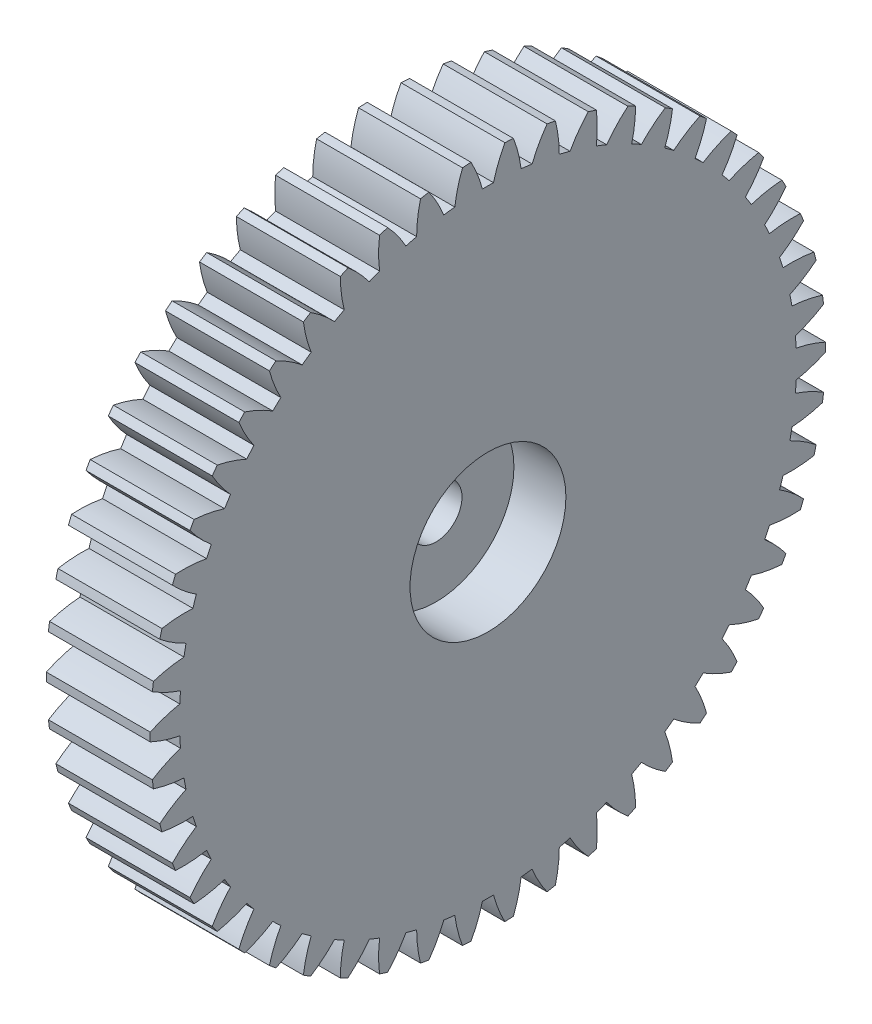
SolidWorks part; units mm, degrees
material "ABS"
ref_plane "Plane1" through (0, 0, 0) normal (0, 0, 1) x (1, 0, 0)
ref_plane "Plane2" through (0, 0, 0) normal (0, 1, 0) x (1, 0, 0)
ref_plane "Plane3" through (0, 0, 0) normal (1, 0, 0) x (0, 0, -1)
sketch "HoldingSke" plane through (0, 0, 0) normal (0, 1, 0) x (1, 0, 0)
  line L0 (0, 0) -> (2.5712, -3.0642)
  line L1 (-15, 0) -> (100, 0) construction
  line L2 (0, 0) -> (-2.1039, 2.3779)
  line L3 (0, 0) -> (-11.863, 4.5341)
  line L4 (0, 0) -> (5.5511, 6.6156)
  line L5 (0, 0) -> (-46.8476, -17.4728)
  line L6 (0, 0) -> (-1.6579, -1.1186)
  line L7 (-2.1039, 2.3779) -> (8.6586, 51.2059)
  line L8 (-76.2, 54.61) -> (-76.1, 54.61)
  line L9 (-71.009, 38.7566) -> (-53.1078, 45.2721)
  line L10 (-76.2, 71.12) -> (104.1128, 71.12)
  line L11 (0, 0) -> (-2, 0)
  line L12 (-76.2, 101.6) -> (-76.192, 101.6)
  line L13 (24.9733, 27.94) -> (52.9518, 28.4284)
  line L14 (24.9733, 27.94) -> (24.9743, 27.94)
  line L15 (24.9733, 27.94) -> (100.4006, 29.5858)
  line L16 (-63.627, -0.25) -> (-12.827, -0.25)
  circle A0 centre (0, 0) radius 0.5
  circle A1 centre (0, 0) radius 5.9365
  circle A2 centre (0, 0) radius 37.5
  circle A3 centre (0, 0) radius 0.5
  dimension "MHD" = 11.873
  dimension "Hub_dia" = 75
  dimension "Bore" = 1
  dimension "MBD" = 1
  dimension "Num_teeth" = 50
  dimension "Pitch" = 4
  dimension "Overall_len" = 50
  dimension "Show_teeth" = 50
  dimension "Thickness" = 2
  dimension "OAL" = 50.0001
  dimension "T_dim" = 0.1
  dimension "Ap" = 20
  dimension "H" = 19.05
  dimension "Pitch_radius" = 180.3128
  dimension "Width" = 2
  dimension "Backlash" = 0.008
  dimension "Addendum_fac" = 1
  dimension "Dedendum_fac" = 1.25
  dimension "Clearance_fac" = 0.25
  dimension "Dedendum_add" = 0.001
  dimension "Module" = 0.25
sketch "BasProSke" plane through (0, 0, 0) normal (0, 1, 0) x (1, 0, 0)
  line L0 (-10, 0) -> (60, 0) construction
  line L1 (0, 0) -> (0, 6.5)
  line L2 (0, 0) -> (2, 0)
  line L3 (2, 0) -> (2, 6.5)
  line L4 (2, 6.5) -> (0, 6.5)
  dimension "Thickness" = 2
  dimension "Diameter" = 13
revolve "Base-Revolve" add sketch "BasProSke" angle 360 about L0
sketch "TooCutSke" plane through (0, 0, 0) normal (1, 0, 0) x (0, 0, -1)
  line L1 (0, 0) -> (0, 107) construction
  line L2 (0, 0) -> (-0.2103, 6.2465) construction
  line L3 (0, 0) -> (-0.7845, 12.47) construction
  line L4 (-0.2103, 6.2465) -> (-0.3923, 6.235) construction
  arc A0 (0.1067, 5.9355) -> (-0.1067, 5.9355) centre (0, 0) ccw
  arc A1 (0.3398, 6.5165) -> (-0.3398, 6.5165) centre (0, 0) ccw
  circle A2 centre (0, 0) radius 6.25 construction
  circle A3 centre (0, 0) radius 5.8731 construction
  arc A4 (-0.1067, 5.9355) -> (-0.3398, 6.5165) centre (-2.5252, 5.3025) ccw
  arc A5 (0.3398, 6.5165) -> (0.1067, 5.9355) centre (2.5252, 5.3025) ccw
  dimension "Root_dia" = 11.873
  dimension "Overcut_dia" = 13.0508
  dimension "Pitch_dia" = 12.5
  dimension "Base_dia" = 11.7462
  dimension "Flank_rad" = 2.5
  dimension "Half_ang" = 3.6
  dimension "Half_CT" = 0.1823
extrude "ToothCut" cut sketch "TooCutSke" along normal through all
fillet "Breaks" [suppressed] radius 0.005
fillet "RootFillets" [suppressed] radius 0.0635
pattern_circular "TeethCuts" count 50 every 7.2 about axis through (-10, 0, 0) along (1, 0, 0) of "ToothCut", "RootFillets", "Breaks"
sketch "HubNeaOneSke" plane through (0, 0, 0) normal (-1, 0, 0) x (0, 0, 1)
  circle A0 centre (0, 0) radius 5.9365
  dimension "Diameter" = 11.873
extrude "HubNearOne" [suppressed] add sketch "HubNeaOneSke" along normal blind 48.0001
sketch "HubNeaBotSke" plane through (0, 0, 0) normal (-1, 0, 0) x (0, 0, 1)
  circle A0 centre (0, 0) radius 5.9365
  dimension "Diameter" = 11.873
extrude "HubNearBoth" [suppressed] add sketch "HubNeaBotSke" along normal blind 24
ref_plane "FarPln" through (2, 0, 0) normal (1, 0, 0) x (0, 0, -1)
sketch "HubFarSke" plane through (2, 0, 0) normal (1, 0, 0) x (0, 0, -1)
  circle A0 centre (0, 0) radius 5.9365
  dimension "Diameter" = 11.873
extrude "HubFar" [suppressed] add sketch "HubFarSke" along normal blind 24
sketch "BorSke" plane through (0, 0, 0) normal (1, 0, 0) x (0, 0, -1)
  circle A0 centre (0, 0) radius 0.5
  dimension "Diameter" = 1
extrude "Bore" cut sketch "BorSke" along normal mid plane 100.0001
sketch "KeySke" plane through (0, 0, 0) normal (1, 0, 0) x (0, 0, -1)
  line L0 (-0.05, 0) -> (-0.05, 0.6)
  line L1 (-0.05, 0.6) -> (0.05, 0.6)
  line L2 (0.05, 0.6) -> (0.05, 0)
  line L3 (0, 0) -> (0, 34) construction
  line L4 (-0.05, 0) -> (0.05, 0)
  dimension "Offset" = 0.6
  dimension "Width" = 0.1
extrude "Keyway" [suppressed] cut sketch "KeySke" along normal mid plane 100.0001
pattern_circular "Keyway2" [suppressed] count 2 every 90 about axis through (-10, 0, 0) along (1, 0, 0)
sketch "Sketch1" plane through (2, 0, 0) normal (1, 0, 0) x (0, 0, -1)
  circle A0 centre (0, 0) radius 1.5
  dimension "D1" = 3
extrude "Cut-Extrude1" cut sketch "Sketch1" against normal blind 1
equation "' \"Module@HoldingSke\" = 6.35"
equation "' \"Num_teeth@HoldingSke\" = 12"
equation "' \"Ap@HoldingSke\" =  20"
equation "' \"Ap@HoldingSke\" = 20"
equation "' \"Width@HoldingSke\" = 0.5 * 25.4"
equation "' \"Hub_dia@HoldingSke\"= 1 * 25.4"
equation "' \"Hub_dia@HoldingSke\" = 1 * 25.4"
equation "' \"Overall_len@HoldingSke\" = 1.0 * 25.4"
equation "' \"Bore@HoldingSke\" = 0.75 * 25.4"
equation "' \"T_dim@HoldingSke\" = 0.1 * 25.4"
equation "' \"Width@KeySke\" = 0.25 * 25.4"
equation "' \"Show_teeth@HoldingSke\" = 13"
equation "' \"Backlash@HoldingSke\" = 0.009 * 25.4"
equation "' \"Addendum_fac@HoldingSke\" = 1.0"
equation "' \"Dedendum_fac@HoldingSke\" = 1.25"
equation "' \"Dedendum_add@HoldingSke\" = 0.00005 * 25.4"
equation "' \"Clearance_fac@HoldingSke\" = 0.25"
equation "\"Pitch@HoldingSke\" = 1 / \"Module@HoldingSke\""
equation "\"Overcut_dia@TooCutSke\" = (\"Num_teeth@HoldingSke\" + 2 * \"Addendum_fac@HoldingSke\") / \"Pitch@HoldingSke\" + 0.002 * 25.4"
equation "\"Pitch_dia@TooCutSke\" = \"Num_teeth@HoldingSke\" / \"Pitch@HoldingSke\""
equation "\"Base_dia@TooCutSke\" = \"Num_teeth@HoldingSke\" / \"Pitch@HoldingSke\" * cos((\"Ap@HoldingSke\"  * 3.14159265 / 180))"
equation "\"Root_dia@TooCutSke\" = (\"Num_teeth@HoldingSke\" + 2) / \"Pitch@HoldingSke\" - 2 * (\"Addendum_fac@HoldingSke\" + \"Dedendum_fac@HoldingSke\") / \"Pitch@HoldingSke\" - \"Dedendum_add@HoldingSke\" * 2"
equation "\"Half_ang@TooCutSke\" = 180 / \"Num_teeth@HoldingSke\""
equation "\"Half_CT@TooCutSke\" = \"Num_teeth@HoldingSke\" / \"Pitch@HoldingSke\" * sin((3.14159265 / 2 / \"Num_teeth@HoldingSke\")) / 2 - 7 * \"Backlash@HoldingSke\" / 4"
equation "\"Flank_rad@TooCutSke\" = \"Num_teeth@HoldingSke\" / \"Pitch@HoldingSke\" / 5"
equation "\"Radius@RootFillets\" = \"Clearance_fac@HoldingSke\" / \"Pitch@HoldingSke\" + \"Dedendum_add@HoldingSke\""
equation "\"Break_rad@Breaks\" = 0.02 / \"Pitch@HoldingSke\""
equation "\"Thickness@HoldingSke\" = \"Width@HoldingSke\""
equation "\"OAL@HoldingSke\" = \"Thickness@HoldingSke\""
equation "\"MHD@HoldingSke\" = (\"Num_teeth@HoldingSke\" + 2) / \"Pitch@HoldingSke\" - 2 * (\"Addendum_fac@HoldingSke\" + \"Dedendum_fac@HoldingSke\")  / \"Pitch@HoldingSke\" - \"Dedendum_add@HoldingSke\" * 2"
equation "\"MBD@HoldingSke\" = (\"Num_teeth@HoldingSke\" + 2) / \"Pitch@HoldingSke\" - 2 * (\"Addendum_fac@HoldingSke\" + \"Dedendum_fac@HoldingSke\")  / \"Pitch@HoldingSke\" - \"Dedendum_add@HoldingSke\" * 2 - 0.002 * 25.4"
equation "\"MHD@HoldingSke\" = ((sgn( \"MHD@HoldingSke\" - \"Hub_dia@HoldingSke\" )-1)*( \"MHD@HoldingSke\" - \"Hub_dia@HoldingSke\" ))/-2+ \"Hub_dia@HoldingSke\""
equation "\"MBD@HoldingSke\" = ((sgn( \"MBD@HoldingSke\" - \"Bore@HoldingSke\" )-1)*( \"MBD@HoldingSke\" - \"Bore@HoldingSke\" ))/-2+ \"Bore@HoldingSke\""
equation "\"OAL@HoldingSke\" = ((sgn( \"OAL@HoldingSke\" - \"Overall_len@HoldingSke\" )+1)*( \"OAL@HoldingSke\" - \"Overall_len@HoldingSke\" ))/2 + \"Overall_len@HoldingSke\" + 0.000002 * 25.4"
equation "\"Num_teeth@TeethCuts\" = int( \"Show_teeth@HoldingSke\" ) + 1"
equation "\"Num_teeth@TeethCuts\" = ((sgn( \"Num_teeth@TeethCuts\" - \"Num_teeth@HoldingSke\" )-1)*( \"Num_teeth@TeethCuts\" - \"Num_teeth@HoldingSke\" ))/-2+ \"Num_teeth@HoldingSke\""
equation "\"Num_teeth@TeethCuts\" = ((sgn( \"Num_teeth@TeethCuts\" - 2.0)+1)*( \"Num_teeth@TeethCuts\" - 2.0))/2 +2.0"
equation "\"Angle@TeethCuts\" = 360.0 / \"Num_teeth@HoldingSke\""
equation "\"Diameter@BasProSke\" = (\"Num_teeth@HoldingSke\" + 2 * \"Addendum_fac@HoldingSke\") / \"Pitch@HoldingSke\""
equation "\"Thickness@BasProSke\"  = \"Thickness@HoldingSke\""
equation "' \"Fillet_rad@BasProSke\" =  \"Thickness@HoldingSke\" * 0.05"
equation "' \"Fillet_rad@BasProSke\" = \"Thickness@HoldingSke\" * 0.05"
equation "\"MHD@HoldingSke\" = ((sgn( \"MHD@HoldingSke\" - \"Root_dia@TooCutSke\" )-1)*( \"MHD@HoldingSke\" - \"Root_dia@TooCutSke\" ))/-2+ \"Root_dia@TooCutSke\""
equation "\"Diameter@HubNeaOneSke\" = \"MHD@HoldingSke\""
equation "\"Length@HubNearOne\" = \"OAL@HoldingSke\" - \"Thickness@BasProSke\""
equation "\"Diameter@HubNeaBotSke\" = \"MHD@HoldingSke\""
equation "\"Length@HubNearBoth\" = ( \"OAL@HoldingSke\" - \"Thickness@BasProSke\" ) / 2.0"
equation "\"Thickness@FarPln\" = \"Thickness@BasProSke\""
equation "\"Diameter@HubFarSke\" = \"MHD@HoldingSke\""
equation "\"Length@HubFar\" = ( \"OAL@HoldingSke\" - \"Thickness@BasProSke\" ) / 2.0"
equation "\"Diameter@BorSke\" = \"MBD@HoldingSke\""
equation "\"D1@Bore\" = \"OAL@HoldingSke\" * 2.0"
equation "\"D1@Keyway\" = \"OAL@HoldingSke\" * 2.0"
equation "\"Offset@KeySke\" = \"T_dim@HoldingSke\" + \"MBD@HoldingSke\" / 2.0"
